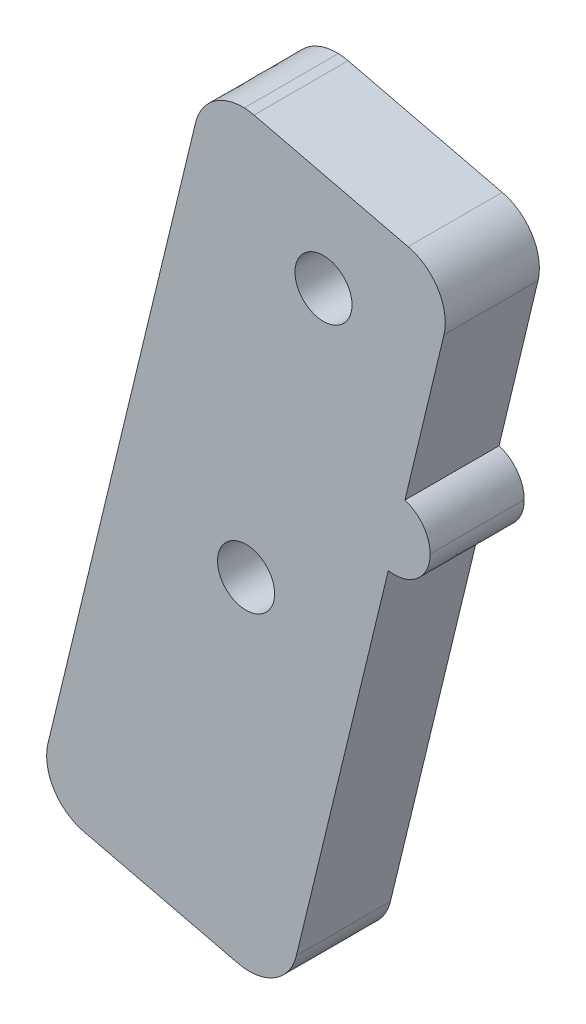
SolidWorks part; units mm, degrees
ref_plane "Front Plane" through (0, 0, 0) normal (0, 0, 1) x (1, 0, 0)
ref_plane "Top Plane" through (0, 0, 0) normal (0, 1, 0) x (1, 0, 0)
ref_plane "Right Plane" through (0, 0, 0) normal (1, 0, 0) x (0, 0, -1)
sketch "Model" plane through (0, 0, 0) normal (0, 0, 1) x (1, 0, 0)
  line L201 (-262.8855, 77.7663) -> (-272.8434, 36.5132)
  line L202 (-270.4236, 32.5666) -> (-260.0278, 30.0723)
  line L203 (-256.0795, 32.4923) -> (-249.8766, 58.0964)
  line L204 (-248.7524, 62.7785) -> (-246.1231, 73.7453)
  line L205 (-248.5431, 77.6932) -> (-258.9389, 80.1862)
  circle A0 centre (-254.2529, 72.3954) radius 1.9251
  circle A1 centre (-259.4756, 52.9045) radius 1.9251
  spline S436 degree 3 poles (-259.5963, 80.2772) (-261.1217, 80.3295) (-262.5167, 79.3095) (-262.8855, 77.7663) knots 0 0 0 0 0.071429 0.071429 0.071429 0.071429
  spline S437 degree 3 poles (-272.8434, 36.5132) (-273.2663, 34.7494) (-272.1875, 32.9898) (-270.4236, 32.5666) knots 0.142857 0.142857 0.142857 0.142857 0.214286 0.214286 0.214286 0.214286
  spline S438 degree 3 poles (-260.0278, 30.0723) (-258.2636, 29.6496) (-256.5027, 30.7281) (-256.0795, 32.4923) knots 0.285714 0.285714 0.285714 0.285714 0.357143 0.357143 0.357143 0.357143
  spline S439 degree 3 poles (-249.8766, 58.0964) (-249.742, 58.0727) (-249.6054, 58.0619) (-249.4692, 58.0619) knots 0.428571 0.428571 0.428571 0.428571 0.5 0.5 0.5 0.5
  spline S440 degree 3 poles (-249.4692, 58.0619) (-248.1365, 58.0619) (-247.0559, 59.1417) (-247.0559, 60.4748) knots 0.5 0.5 0.5 0.5 0.571429 0.571429 0.571429 0.571429
  spline S441 degree 3 poles (-247.0559, 60.4748) (-247.0559, 61.5318) (-247.744, 62.4645) (-248.7524, 62.7785) knots 0.571429 0.571429 0.571429 0.571429 0.642857 0.642857 0.642857 0.642857
  spline S442 degree 3 poles (-246.1231, 73.7453) (-245.7003, 75.5091) (-246.7789, 77.27) (-248.5431, 77.6932) knots 0.714286 0.714286 0.714286 0.714286 0.785714 0.785714 0.785714 0.785714
  spline S443 degree 3 poles (-258.9389, 80.1862) (-259.1594, 80.2398) (-259.3787, 80.2689) (-259.5963, 80.2772) knots 0.857143 0.857143 0.857143 0.857143 1 1 1 1
extrude "Boss-Extrude1" add sketch "Model" along normal blind 6.35
